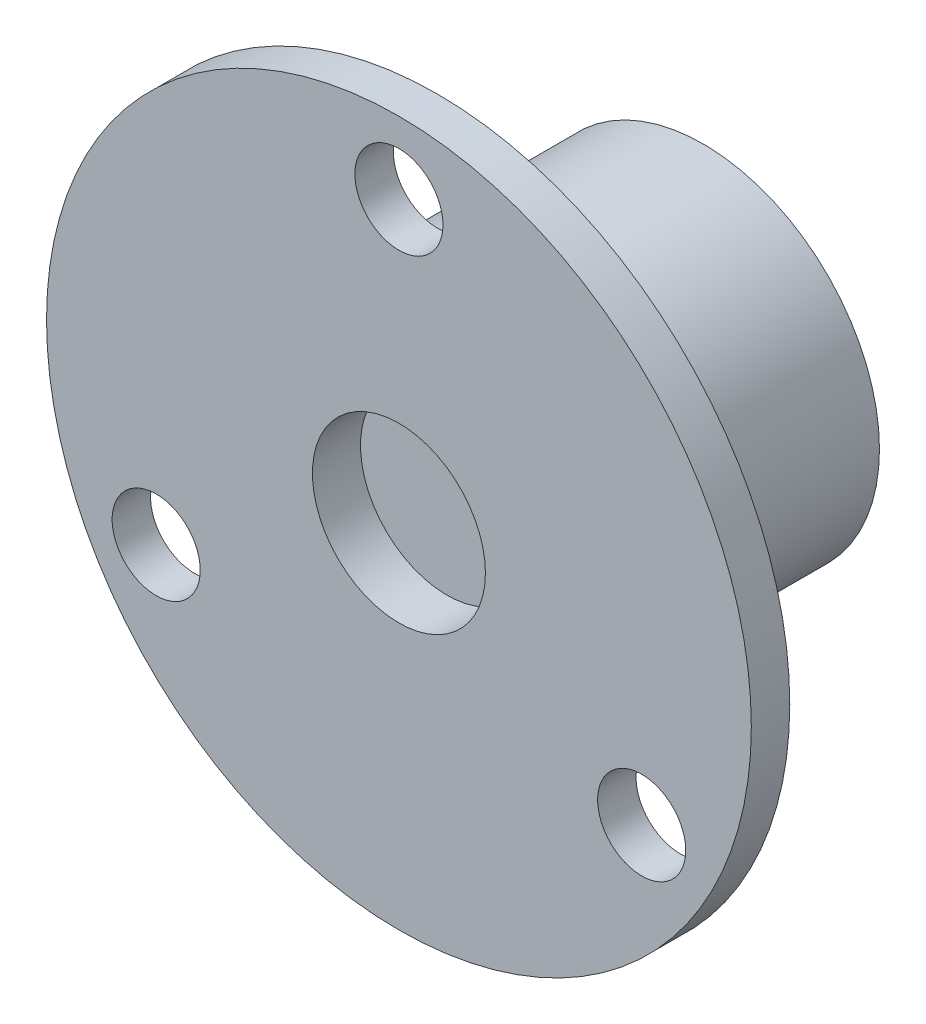
SolidWorks part; units mm, degrees
ref_plane "Front Plane" through (0, 0, 0) normal (0, 0, 1) x (1, 0, 0)
ref_plane "Top Plane" through (0, 0, 0) normal (0, 1, 0) x (1, 0, 0)
ref_plane "Right Plane" through (0, 0, 0) normal (1, 0, 0) x (0, 0, -1)
sketch "Sketch1" plane through (0, 0, 0) normal (0, 0, 1) x (1, 0, 0)
  circle A0 centre (0, 0) radius 22
  circle A1 centre (0, 0) radius 11
  dimension "D1" = 44
extrude "Boss-Extrude1" add sketch "Sketch1" along normal blind 2.4
sketch "Sketch2" plane through (0, 0, 2.4) normal (0, 0, 1) x (1, 0, 0)
  circle A0 centre (0, 0) radius 17.5
  circle A1 centre (0, 17.5) radius 2.75
  circle A2 centre (15.1554, -8.75) radius 2.75
  circle A3 centre (-15.1554, -8.75) radius 2.75
  point P11 (0, 0)
  dimension "D1" = 35
  dimension "D2" = 3
extrude "Cut-Extrude1" cut sketch "Sketch2" against normal through all contours A1 | A3 | A2
sketch "Sketch4" plane through (0, 0, 2.4) normal (0, 0, 1) x (1, 0, 0)
  circle A0 centre (0, 0) radius 11
extrude "Boss-Extrude4" add sketch "Sketch4" against normal blind 19
sketch "Sketch6" plane through (0, 0, 2.4) normal (0, 0, 1) x (1, 0, 0)
  circle A0 centre (0, 0) radius 5.4
  dimension "D1" = 10.8
extrude "Cut-Extrude2" cut sketch "Sketch6" against normal blind 3 contours A0
